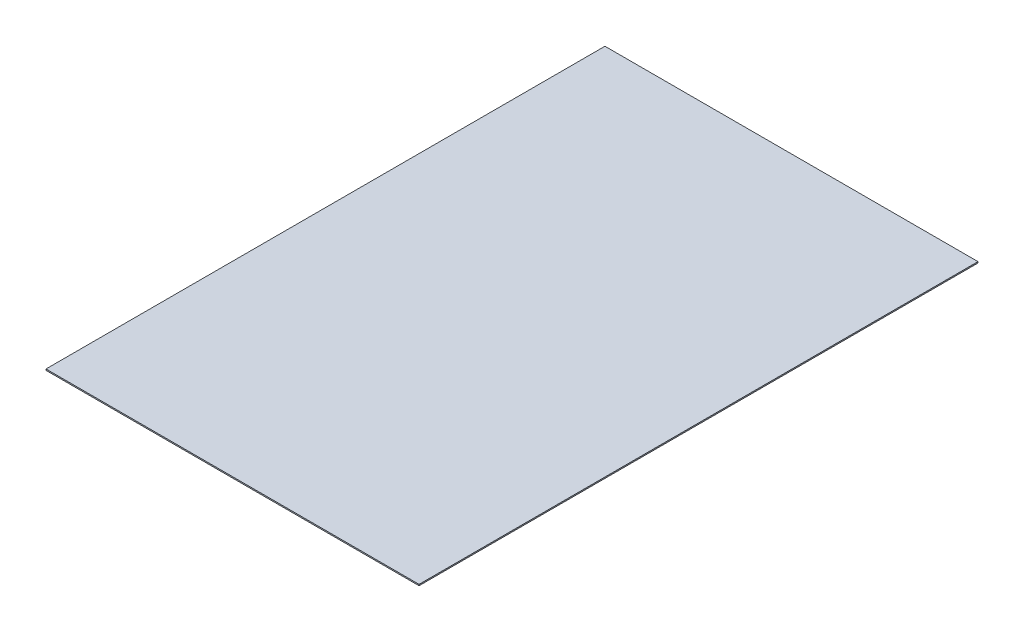
SolidWorks part; units mm, degrees
ref_plane "Front Plane" through (0, 0, 0) normal (0, 0, 1) x (1, 0, 0)
ref_plane "Top Plane" through (0, 0, 0) normal (0, 1, 0) x (1, 0, 0)
ref_plane "Right Plane" through (0, 0, 0) normal (1, 0, 0) x (0, 0, -1)
sketch "Sketch1" plane through (0, 0, 0) normal (0, 1, 0) x (1, 0, 0)
  line L1 (76.2, 0) -> (0, 0)
  line L2 (76.2, 0) -> (76.2, 114.173)
  line L3 (76.2, 114.173) -> (0, 114.173)
  line L4 (0, 0) -> (0, 114.173)
extrude "Boss-Extrude1" add sketch "Sketch1" along normal blind 0.254
